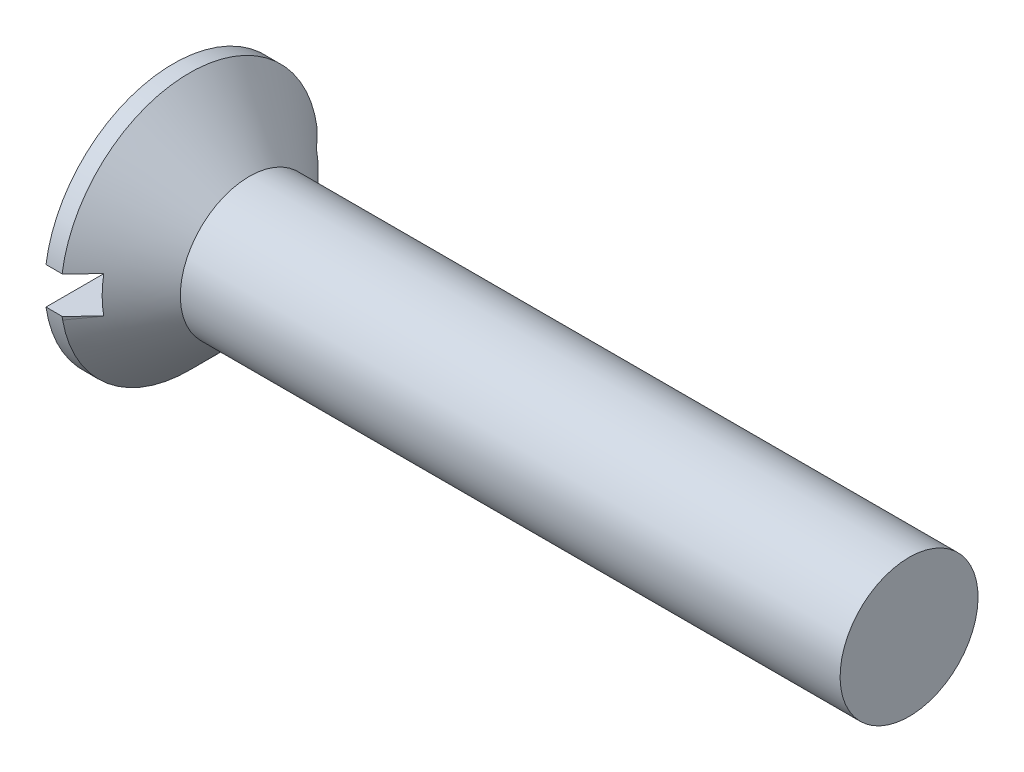
SolidWorks part; units mm, degrees
material "Plain Carbon Steel"
ref_plane "Front Plane" through (0, 0, 0) normal (0, 0, 1) x (1, 0, 0)
ref_plane "Top Plane" through (0, 0, 0) normal (0, 1, 0) x (1, 0, 0)
ref_plane "Right Plane" through (0, 0, 0) normal (1, 0, 0) x (0, 0, -1)
sketch "Sketch1" plane through (0, 0, 0) normal (0, 0, 1) x (1, 0, 0)
  line L0 (0, 0) -> (0, 2.8)
  line L1 (0, 2.8) -> (0.35, 2.8)
  line L2 (0.35, 2.8) -> (1.65, 1.5)
  line L3 (1.65, 1.5) -> (16, 1.5)
  line L4 (16, 1.5) -> (16, 0)
  line L5 (16, 0) -> (0, 0) construction
  line L6 (0, 0) -> (16, 0)
  dimension "D1" = 45
  dimension "D2" = 3
  dimension "D3" = 5.6
  dimension "D4" = 1.65
  dimension "D5" = 16
revolve "Revolve1" add sketch "Sketch1" angle 360 about L5
sketch "Sketch2" plane through (0, 0, 0) normal (-1, 0, 0) x (0, 0, 1)
  line L0 (2.8, 0) -> (-2.8, 0) construction
  line L1 (-2.8, 0.4) -> (2.8, 0.4)
  line L2 (-2.8, 0.4) -> (-2.8, -0.4)
  line L3 (-2.8, -0.4) -> (2.8, -0.4)
  line L4 (2.8, 0.4) -> (2.8, -0.4)
  circle A0 centre (0, 0) radius 2.8 construction
  dimension "D1" = 0.8
extrude "Cut-Extrude1" cut sketch "Sketch2" against normal blind 0.8
